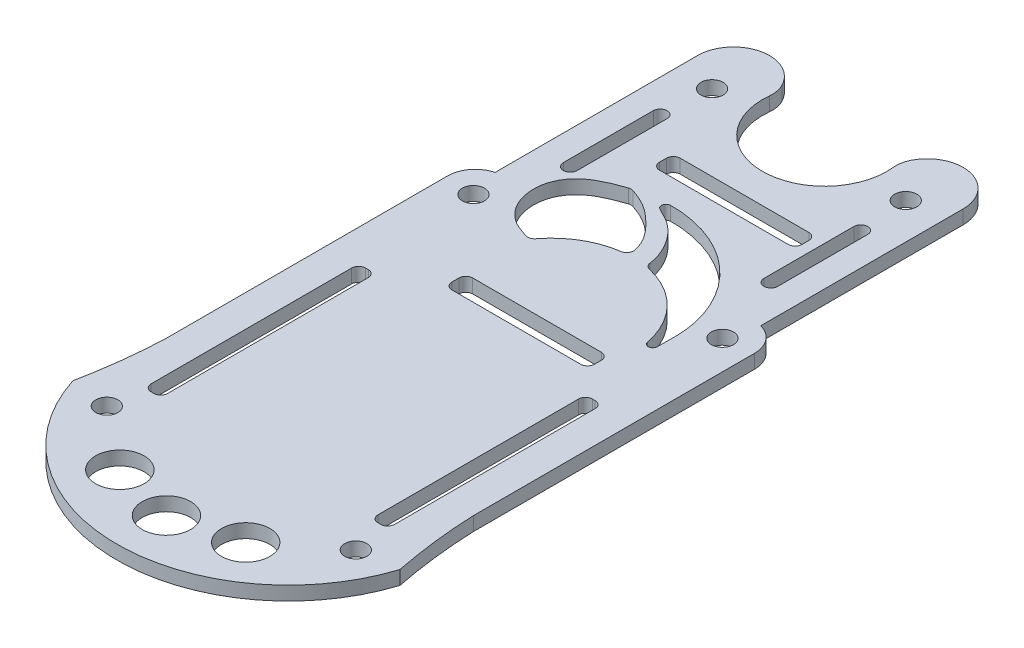
SolidWorks part; units mm, degrees
ref_plane "Front Plane" through (0, 0, 0) normal (0, 0, 1) x (1, 0, 0)
ref_plane "Top Plane" through (0, 0, 0) normal (0, 1, 0) x (1, 0, 0)
ref_plane "Right Plane" through (0, 0, 0) normal (1, 0, 0) x (0, 0, -1)
sketch "Sketch1" plane through (0, 0, 0) normal (0, 1, 0) x (1, 0, 0)
  line L0 (-23.6701, -32.0564) -> (-23.6701, 8.6189)
  line L1 (-20.6701, 12.4977) -> (-20.6701, 41.7649)
  line L2 (17.7299, 41.7649) -> (17.7299, 12.4977)
  line L3 (20.7299, 8.6189) -> (20.7299, -32.0564)
  line L4 (-16.9701, 31.6607) -> (-16.9701, 18.6607)
  line L5 (-14.9701, 18.6607) -> (-14.9701, 31.6607)
  line L6 (12.0299, 31.6607) -> (12.0299, 18.6607)
  line L7 (14.0299, 18.6607) -> (14.0299, 31.6607)
  line L8 (13.7299, -9.8393) -> (13.7299, -38.8393)
  line L9 (16.1299, -9.8393) -> (16.1299, -38.8393)
  line L10 (14.7299, -8.8393) -> (15.1299, -8.8393)
  line L11 (14.7299, -39.8393) -> (15.1299, -39.8393)
  line L12 (-16.6701, -9.8393) -> (-16.6701, -38.8393)
  line L13 (-19.0701, -9.8393) -> (-19.0701, -38.8393)
  line L14 (-17.6701, -8.8393) -> (-18.0701, -8.8393)
  line L15 (-17.6701, -39.8393) -> (-18.0701, -39.8393)
  line L16 (-9.0701, 24.6607) -> (9.5299, 24.6607)
  line L17 (-9.0701, 27.6607) -> (9.5299, 27.6607)
  line L18 (10.5299, 26.6607) -> (10.5299, 25.6607)
  line L19 (-10.0701, 26.6607) -> (-10.0701, 25.6607)
  line L20 (-9.0701, -5.3393) -> (9.5299, -5.3393)
  line L21 (-9.0701, -2.3393) -> (9.5299, -2.3393)
  line L22 (10.5299, -3.3393) -> (10.5299, -4.3393)
  line L23 (-10.0701, -3.3393) -> (-10.0701, -4.3393)
  circle A0 centre (-1.4701, -54.219) radius 3.5
  circle A1 centre (7.6299, -51.8583) radius 3.5
  circle A2 centre (-10.5701, -51.8583) radius 3.5
  circle A3 centre (-19.4701, -44.8393) radius 1.6
  circle A4 centre (16.5299, -44.8393) radius 1.6
  circle A5 centre (-19.4701, 8.1607) radius 1.6
  circle A6 centre (16.5299, 8.1607) radius 1.6
  circle A7 centre (-15.4701, 38.6607) radius 1.599
  circle A8 centre (12.5299, 38.6607) radius 1.599
  arc A9 (20.7299, -32.0564) -> (22.1649, -44.1011) centre (97.7098, -28.9928) ccw
  arc A10 (-25.1051, -44.1011) -> (22.1649, -44.1011) centre (-1.4701, -36.5893) ccw
  arc A11 (-25.1051, -44.1011) -> (-23.6701, -32.0564) centre (-100.65, -28.9928) ccw
  arc A12 (-21.2701, 12.285) -> (-23.6701, 8.6189) centre (-19.6701, 8.6189) ccw
  arc A13 (-20.6701, 12.4977) -> (-21.2701, 12.285) centre (-19.4701, 8.1607) ccw
  arc A14 (-10.8289, 44.11) -> (-20.6701, 41.7649) centre (-15.4701, 41.7649) ccw
  arc A15 (-10.4209, 41.8885) -> (-10.8289, 44.11) centre (-14.3991, 42.3061) ccw
  arc A16 (-10.4209, 41.8885) -> (7.4807, 41.8885) centre (-1.4701, 40.9489) ccw
  arc A17 (7.8887, 44.11) -> (7.4807, 41.8885) centre (11.4589, 42.3061) ccw
  arc A18 (17.7299, 41.7649) -> (7.8887, 44.11) centre (12.5299, 41.7649) ccw
  arc A19 (18.3299, 12.285) -> (17.7299, 12.4977) centre (16.5299, 8.1607) ccw
  arc A20 (20.7299, 8.6189) -> (18.3299, 12.285) centre (16.7299, 8.6189) ccw
  arc A21 (-16.9701, 18.6607) -> (-14.9701, 18.6607) centre (-15.9701, 18.6607) ccw
  arc A22 (-14.9701, 31.6607) -> (-16.9701, 31.6607) centre (-15.9701, 31.6607) ccw
  arc A23 (12.0299, 18.6607) -> (14.0299, 18.6607) centre (13.0299, 18.6607) ccw
  arc A24 (14.0299, 31.6607) -> (12.0299, 31.6607) centre (13.0299, 31.6607) ccw
  arc A25 (16.1299, -9.8393) -> (15.1299, -8.8393) centre (15.1299, -9.8393) ccw
  arc A26 (14.7299, -8.8393) -> (13.7299, -9.8393) centre (14.7299, -9.8393) ccw
  arc A27 (15.1299, -39.8393) -> (16.1299, -38.8393) centre (15.1299, -38.8393) ccw
  arc A28 (13.7299, -38.8393) -> (14.7299, -39.8393) centre (14.7299, -38.8393) ccw
  arc A29 (-18.0701, -8.8393) -> (-19.0701, -9.8393) centre (-18.0701, -9.8393) ccw
  arc A30 (-16.6701, -9.8393) -> (-17.6701, -8.8393) centre (-17.6701, -9.8393) ccw
  arc A31 (-19.0701, -38.8393) -> (-18.0701, -39.8393) centre (-18.0701, -38.8393) ccw
  arc A32 (-17.6701, -39.8393) -> (-16.6701, -38.8393) centre (-17.6701, -38.8393) ccw
  arc A33 (9.5299, 24.6607) -> (10.5299, 25.6607) centre (9.5299, 25.6607) ccw
  arc A34 (-10.0701, 25.6607) -> (-9.0701, 24.6607) centre (-9.0701, 25.6607) ccw
  arc A35 (10.5299, 26.6607) -> (9.5299, 27.6607) centre (9.5299, 26.6607) ccw
  arc A36 (-9.0701, 27.6607) -> (-10.0701, 26.6607) centre (-9.0701, 26.6607) ccw
  arc A37 (9.5299, -5.3393) -> (10.5299, -4.3393) centre (9.5299, -4.3393) ccw
  arc A38 (-10.0701, -4.3393) -> (-9.0701, -5.3393) centre (-9.0701, -4.3393) ccw
  arc A39 (10.5299, -3.3393) -> (9.5299, -2.3393) centre (9.5299, -3.3393) ccw
  arc A40 (-9.0701, -2.3393) -> (-10.0701, -3.3393) centre (-9.0701, -3.3393) ccw
  arc A41 (11.5924, 2.2771) -> (2.638, 11.5156) centre (0, 0) ccw
  arc A42 (-1.6894, 11.6925) -> (-9.409, 7.1441) centre (0, 0) ccw
  arc A43 (11.5924, 2.2771) -> (12.88, 2.3872) centre (12.2302, 2.4024) ccw
  arc A44 (-10.5163, 6.7984) -> (-9.409, 7.1441) centre (-10.2055, 7.7489) ccw
  arc A45 (1.87, 12.3589) -> (2.638, 11.5156) centre (2.8613, 12.4904) ccw
  arc A46 (-1.6894, 11.6925) -> (-0.8562, 12.8994) centre (-1.8324, 12.6822) ccw
  arc A47 (-8.4521, 20.1905) -> (-9.073, 20.1954) centre (-8.77, 19.2424) ccw
  arc A48 (-3.8805, 21.0508) -> (-4.1544, 19.8152) centre (-3.8724, 20.4008) ccw
  spline S0 degree 3 poles (12.88, 2.3872) (12.8811, 2.4309) (12.8821, 2.4746) (12.8831, 2.5183) (12.9189, 4.0499) (13.0177, 8.2774) (10.2829, 14.5996) (4.2823, 19.7095) (-0.8972, 21.0507) (-3.7345, 21.0526) (-3.8805, 21.0508) knots -0.13063 -0.13063 -0.13063 -0.13063 0 0 0 4.576467 12.631903 19.610603 27.611731 28.04584 28.04584 28.04584 28.04584
  spline S1 degree 3 poles (-9.073, 20.1954) (-9.924, 19.9248) (-11.4573, 19.3149) (-13.8866, 17.9686) (-15.738, 15.4726) (-15.964, 12.141) (-14.8312, 9.2841) (-12.8035, 7.5462) (-11.3338, 7.0657) (-10.7156, 6.8636) (-10.6491, 6.8418) (-10.5827, 6.8201) (-10.5163, 6.7984) knots 33.278769 33.278769 33.278769 33.278769 35.93277 38.174441 41.57294 44.716598 47.79337 50.469296 52.412007 52.412007 52.412007 52.620772 52.620772 52.620772 52.620772
  spline S2 degree 3 poles (-0.8562, 12.8994) (-0.9193, 13.183) (-1.361, 14.7882) (-3.2205, 16.9953) (-5.6906, 19.1036) (-7.5137, 19.869) (-8.3518, 20.1569) (-8.4521, 20.1905) knots 1.628368 1.628368 1.628368 1.628368 2.50276 6.666081 9.886558 12.220662 12.537413 12.537413 12.537413 12.537413
  spline S3 degree 3 poles (1.87, 12.3589) (1.8427, 12.5649) (1.6458, 13.7725) (0.6431, 16.0737) (-1.3246, 18.3457) (-3.1893, 19.3438) (-3.9724, 19.7276) (-4.1544, 19.8152) knots 1.415794 1.415794 1.415794 1.415794 2.040259 5.0971 8.794779 10.800796 11.405761 11.405761 11.405761 11.405761
sketch "Sketch2" plane through (0, 0, 0) normal (0, 1, 0) x (1, 0, 0)
  line L0 (-23.6701, -32.0564) -> (-23.6701, 8.6189)
  line L1 (-20.6701, 12.4977) -> (-20.6701, 41.7649)
  line L2 (17.7299, 41.7649) -> (17.7299, 12.4977)
  line L3 (20.7299, 8.6189) -> (20.7299, -32.0564)
  line L4 (-16.9701, 31.6607) -> (-16.9701, 18.6607)
  line L5 (-14.9701, 18.6607) -> (-14.9701, 31.6607)
  line L6 (12.0299, 31.6607) -> (12.0299, 18.6607)
  line L7 (14.0299, 18.6607) -> (14.0299, 31.6607)
  line L8 (13.7299, -9.8393) -> (13.7299, -38.8393)
  line L9 (16.1299, -9.8393) -> (16.1299, -38.8393)
  line L10 (14.7299, -8.8393) -> (15.1299, -8.8393)
  line L11 (14.7299, -39.8393) -> (15.1299, -39.8393)
  line L12 (-16.6701, -9.8393) -> (-16.6701, -38.8393)
  line L13 (-19.0701, -9.8393) -> (-19.0701, -38.8393)
  line L14 (-17.6701, -8.8393) -> (-18.0701, -8.8393)
  line L15 (-17.6701, -39.8393) -> (-18.0701, -39.8393)
  line L16 (-9.0701, 24.6607) -> (9.5299, 24.6607)
  line L17 (-9.0701, 27.6607) -> (9.5299, 27.6607)
  line L18 (10.5299, 26.6607) -> (10.5299, 25.6607)
  line L19 (-10.0701, 26.6607) -> (-10.0701, 25.6607)
  line L20 (-9.0701, -5.3393) -> (9.5299, -5.3393)
  line L21 (-9.0701, -2.3393) -> (9.5299, -2.3393)
  line L22 (10.5299, -3.3393) -> (10.5299, -4.3393)
  line L23 (-10.0701, -3.3393) -> (-10.0701, -4.3393)
  circle A0 centre (-1.4701, -54.219) radius 3.5
  circle A1 centre (7.6299, -51.8583) radius 3.5
  circle A2 centre (-10.5701, -51.8583) radius 3.5
  circle A3 centre (-19.4701, -44.8393) radius 1.6
  circle A4 centre (16.5299, -44.8393) radius 1.6
  circle A5 centre (-19.4701, 8.1607) radius 1.6
  circle A6 centre (16.5299, 8.1607) radius 1.6
  circle A7 centre (-15.4701, 38.6607) radius 1.599
  circle A8 centre (12.5299, 38.6607) radius 1.599
  arc A9 (20.7299, -32.0564) -> (22.1649, -44.1011) centre (97.7098, -28.9928) ccw
  arc A10 (-25.1051, -44.1011) -> (22.1649, -44.1011) centre (-1.4701, -36.5893) ccw
  arc A11 (-25.1051, -44.1011) -> (-23.6701, -32.0564) centre (-100.65, -28.9928) ccw
  arc A12 (-21.2701, 12.285) -> (-23.6701, 8.6189) centre (-19.6701, 8.6189) ccw
  arc A13 (-20.6701, 12.4977) -> (-21.2701, 12.285) centre (-19.4701, 8.1607) ccw
  arc A14 (-10.8289, 44.11) -> (-20.6701, 41.7649) centre (-15.4701, 41.7649) ccw
  arc A15 (-10.4209, 41.8885) -> (-10.8289, 44.11) centre (-14.3991, 42.3061) ccw
  arc A16 (-10.4209, 41.8885) -> (7.4807, 41.8885) centre (-1.4701, 40.9489) ccw
  arc A17 (7.8887, 44.11) -> (7.4807, 41.8885) centre (11.4589, 42.3061) ccw
  arc A18 (17.7299, 41.7649) -> (7.8887, 44.11) centre (12.5299, 41.7649) ccw
  arc A19 (18.3299, 12.285) -> (17.7299, 12.4977) centre (16.5299, 8.1607) ccw
  arc A20 (20.7299, 8.6189) -> (18.3299, 12.285) centre (16.7299, 8.6189) ccw
  arc A21 (-16.9701, 18.6607) -> (-14.9701, 18.6607) centre (-15.9701, 18.6607) ccw
  arc A22 (-14.9701, 31.6607) -> (-16.9701, 31.6607) centre (-15.9701, 31.6607) ccw
  arc A23 (12.0299, 18.6607) -> (14.0299, 18.6607) centre (13.0299, 18.6607) ccw
  arc A24 (14.0299, 31.6607) -> (12.0299, 31.6607) centre (13.0299, 31.6607) ccw
  arc A25 (16.1299, -9.8393) -> (15.1299, -8.8393) centre (15.1299, -9.8393) ccw
  arc A26 (14.7299, -8.8393) -> (13.7299, -9.8393) centre (14.7299, -9.8393) ccw
  arc A27 (15.1299, -39.8393) -> (16.1299, -38.8393) centre (15.1299, -38.8393) ccw
  arc A28 (13.7299, -38.8393) -> (14.7299, -39.8393) centre (14.7299, -38.8393) ccw
  arc A29 (-18.0701, -8.8393) -> (-19.0701, -9.8393) centre (-18.0701, -9.8393) ccw
  arc A30 (-16.6701, -9.8393) -> (-17.6701, -8.8393) centre (-17.6701, -9.8393) ccw
  arc A31 (-19.0701, -38.8393) -> (-18.0701, -39.8393) centre (-18.0701, -38.8393) ccw
  arc A32 (-17.6701, -39.8393) -> (-16.6701, -38.8393) centre (-17.6701, -38.8393) ccw
  arc A33 (9.5299, 24.6607) -> (10.5299, 25.6607) centre (9.5299, 25.6607) ccw
  arc A34 (-10.0701, 25.6607) -> (-9.0701, 24.6607) centre (-9.0701, 25.6607) ccw
  arc A35 (10.5299, 26.6607) -> (9.5299, 27.6607) centre (9.5299, 26.6607) ccw
  arc A36 (-9.0701, 27.6607) -> (-10.0701, 26.6607) centre (-9.0701, 26.6607) ccw
  arc A37 (9.5299, -5.3393) -> (10.5299, -4.3393) centre (9.5299, -4.3393) ccw
  arc A38 (-10.0701, -4.3393) -> (-9.0701, -5.3393) centre (-9.0701, -4.3393) ccw
  arc A39 (10.5299, -3.3393) -> (9.5299, -2.3393) centre (9.5299, -3.3393) ccw
  arc A40 (-9.0701, -2.3393) -> (-10.0701, -3.3393) centre (-9.0701, -3.3393) ccw
  arc A41 (11.5924, 2.2771) -> (2.638, 11.5156) centre (0, 0) ccw
  arc A42 (-1.6894, 11.6925) -> (-9.409, 7.1441) centre (0, 0) ccw
  arc A43 (11.5924, 2.2771) -> (12.88, 2.3872) centre (12.2302, 2.4024) ccw
  arc A44 (-10.5163, 6.7984) -> (-9.409, 7.1441) centre (-10.2055, 7.7489) ccw
  arc A45 (1.87, 12.3589) -> (2.638, 11.5156) centre (2.8613, 12.4904) ccw
  arc A46 (-1.6894, 11.6925) -> (-0.8562, 12.8994) centre (-1.8324, 12.6822) ccw
  arc A47 (-8.4521, 20.1905) -> (-9.073, 20.1954) centre (-8.77, 19.2424) ccw
  arc A48 (-3.8805, 21.0508) -> (-4.1544, 19.8152) centre (-3.8724, 20.4008) ccw
  spline S0 degree 3 poles (12.88, 2.3872) (12.8811, 2.4309) (12.8821, 2.4746) (12.8831, 2.5183) (12.9189, 4.0499) (13.0177, 8.2774) (10.2829, 14.5996) (4.2823, 19.7095) (-0.8972, 21.0507) (-3.7345, 21.0526) (-3.8805, 21.0508) knots -0.13063 -0.13063 -0.13063 -0.13063 0 0 0 4.576467 12.631903 19.610603 27.611731 28.04584 28.04584 28.04584 28.04584
  spline S1 degree 3 poles (-9.073, 20.1954) (-9.924, 19.9248) (-11.4573, 19.3149) (-13.8866, 17.9686) (-15.738, 15.4726) (-15.964, 12.141) (-14.8312, 9.2841) (-12.8035, 7.5462) (-11.3338, 7.0657) (-10.7156, 6.8636) (-10.6491, 6.8418) (-10.5827, 6.8201) (-10.5163, 6.7984) knots 33.278769 33.278769 33.278769 33.278769 35.93277 38.174441 41.57294 44.716598 47.79337 50.469296 52.412007 52.412007 52.412007 52.620772 52.620772 52.620772 52.620772
  spline S2 degree 3 poles (-0.8562, 12.8994) (-0.9193, 13.183) (-1.361, 14.7882) (-3.2205, 16.9953) (-5.6906, 19.1036) (-7.5137, 19.869) (-8.3518, 20.1569) (-8.4521, 20.1905) knots 1.628368 1.628368 1.628368 1.628368 2.50276 6.666081 9.886558 12.220662 12.537413 12.537413 12.537413 12.537413
  spline S3 degree 3 poles (1.87, 12.3589) (1.8427, 12.5649) (1.6458, 13.7725) (0.6431, 16.0737) (-1.3246, 18.3457) (-3.1893, 19.3438) (-3.9724, 19.7276) (-4.1544, 19.8152) knots 1.415794 1.415794 1.415794 1.415794 2.040259 5.0971 8.794779 10.800796 11.405761 11.405761 11.405761 11.405761
extrude "Boss-Extrude1" add sketch "Sketch2" along normal blind 2
